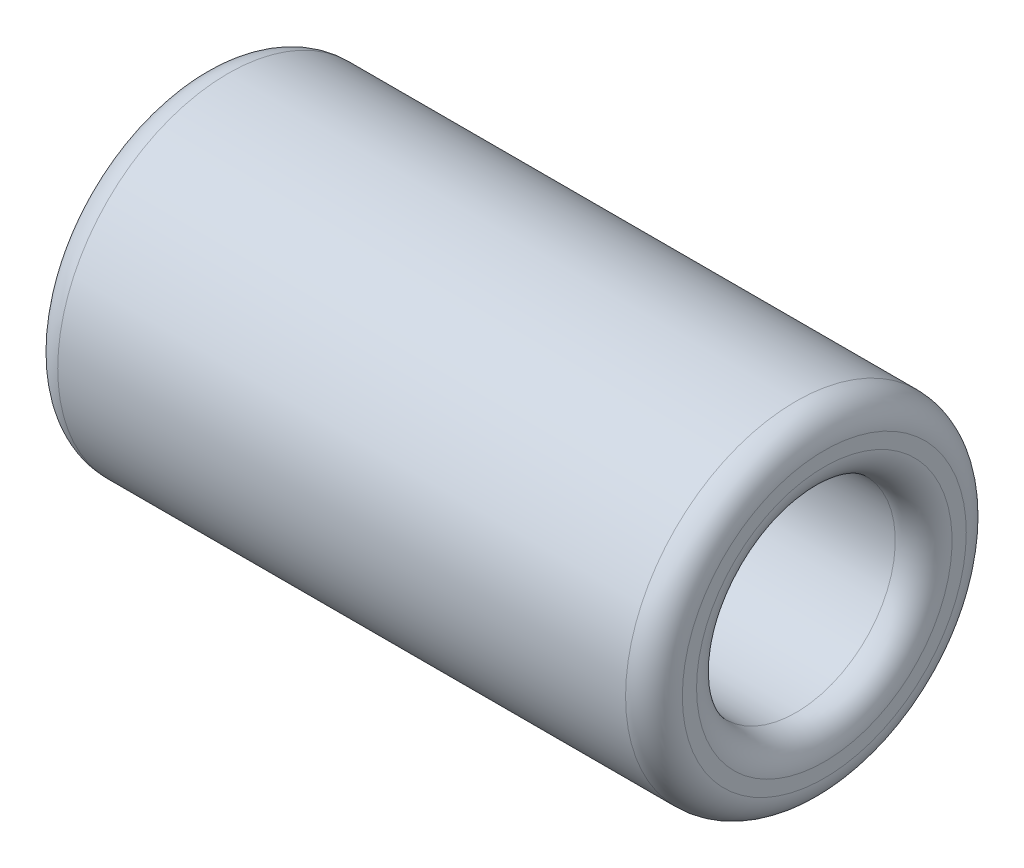
SolidWorks part; units mm, degrees
ref_plane "Ebene vorne" through (0, 0, 0) normal (0, 0, 1) x (1, 0, 0)
ref_plane "Ebene oben" through (0, 0, 0) normal (0, 1, 0) x (1, 0, 0)
ref_plane "Ebene rechts" through (0, 0, 0) normal (1, 0, 0) x (0, 0, -1)
sketch "Sketch1" plane through (0, 0, 0) normal (0, 0, 1) x (1, 0, 0)
  line L0 (0, 0) -> (11, 0) construction
  line L1 (8, 1.9) -> (8.0901, 1.75)
  line L2 (0, 3) -> (11, 3)
  line L3 (0, 3) -> (0, 1.9)
  line L4 (11, 3) -> (11, 1.75)
  line L5 (0, 1.9) -> (8, 1.9)
  line L6 (8.0901, 1.75) -> (11, 1.75)
  dimension "D1" = 6
  dimension "D2" = 3.8
  dimension "D3" = 11
  dimension "D4" = 3.5
  dimension "D5" = 8
  dimension "D6" = 59
revolve "Revolve1" add sketch "Sketch1" angle 360 about L0
fillet "Fillet1" radius 0.5 3 edges at (0, 0, 3) (11, 0, 1.75) (11, 0, 3)
